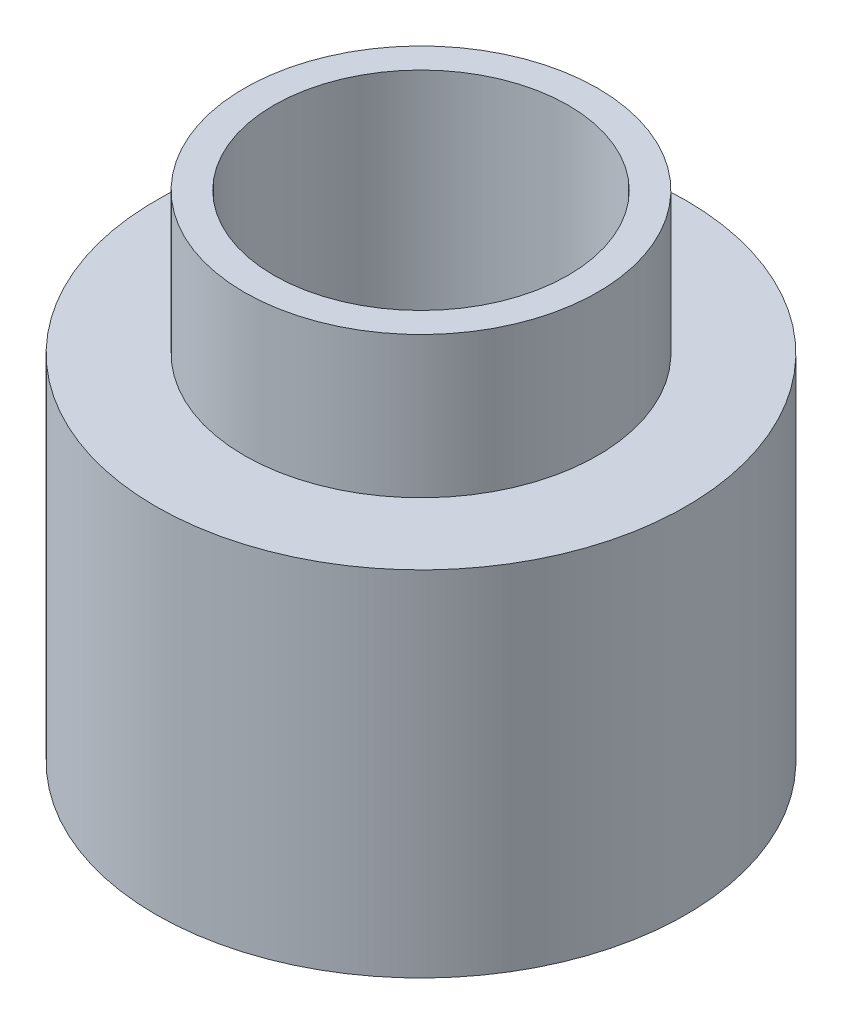
SolidWorks part; units mm, degrees
ref_plane "前视基准面" through (0, 0, 0) normal (0, 0, 1) x (1, 0, 0)
ref_plane "上视基准面" through (0, 0, 0) normal (0, 1, 0) x (1, 0, 0)
ref_plane "右视基准面" through (0, 0, 0) normal (1, 0, 0) x (0, 0, -1)
other "Configuration Table"
sketch "草图1" plane through (0, 0, 0) normal (0, 1, 0) x (1, 0, 0)
  circle A0 centre (0, 0) radius 2.25
  circle A1 centre (0, 0) radius 1.25
  dimension "D1" = 4.5
  dimension "D2" = 2.5
extrude "凸台-拉伸1" add sketch "草图1" along normal blind 3
sketch "草图2" plane through (0, 3, 0) normal (0, 1, 0) x (1, 0, 0)
  circle A0 centre (0, 0) radius 1.25
  circle A1 centre (0, 0) radius 1.5
  dimension "D1" = 3
extrude "凸台-拉伸2" add sketch "草图2" along normal blind 1.2
